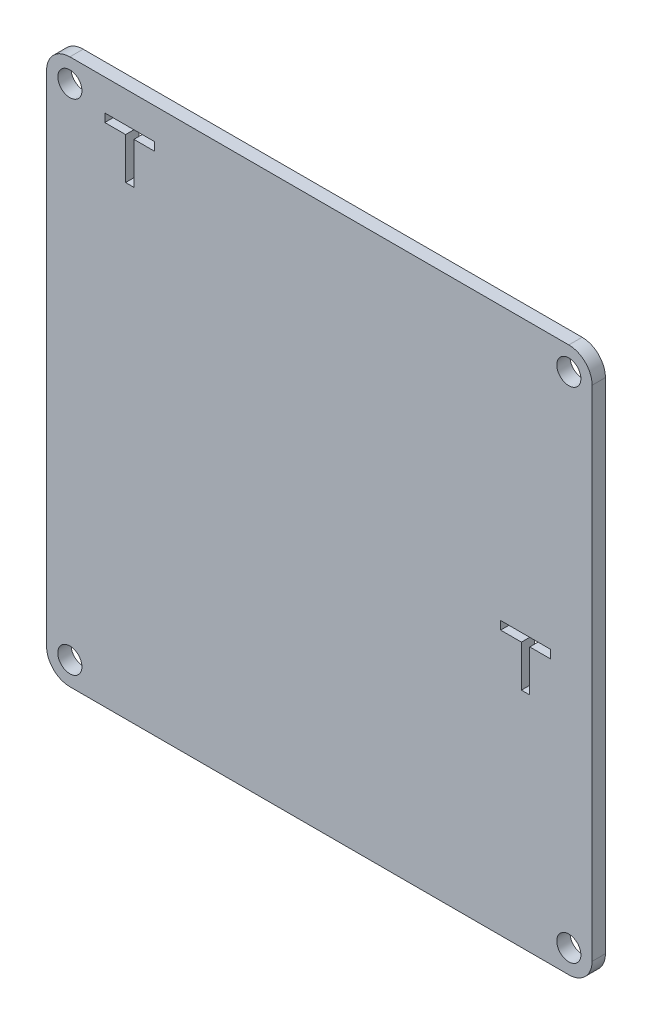
SolidWorks part; units mm, degrees
ref_plane "前视基准面" through (0, 0, 0) normal (0, 0, 1) x (1, 0, 0)
ref_plane "上视基准面" through (0, 0, 0) normal (0, 1, 0) x (1, 0, 0)
ref_plane "右视基准面" through (0, 0, 0) normal (1, 0, 0) x (0, 0, -1)
other "Configuration Table"
sketch "草图1" plane through (0, 0, 0) normal (0, 0, 1) x (1, 0, 0)
  line L1 (-30, 32.8) -> (30, 32.8)
  line L2 (32.8, 30) -> (32.8, -30)
  line L3 (30, -32.8) -> (-30, -32.8)
  line L4 (-32.8, -30) -> (-32.8, 30)
  line L5 (33, -30) -> (33, 30) construction
  arc A0 (30, 32.8) -> (32.8, 30) centre (30, 30) cw
  arc A1 (32.8, -30) -> (30, -32.8) centre (30, -30) cw
  arc A2 (-30, -32.8) -> (-32.8, -30) centre (-30, -30) cw
  arc A3 (-32.8, 30) -> (-30, 32.8) centre (-30, 30) cw
  arc A4 (-30, 33) -> (-33, 30) centre (-30, 30) ccw construction
  arc A6 (33, 30) -> (30, 33) centre (30, 30) ccw construction
  arc A7 (30, -33) -> (33, -30) centre (30, -30) ccw construction
  arc A8 (-33, -30) -> (-30, -33) centre (-30, -30) ccw construction
  circle A9 centre (-30, 30) radius 1.45
  circle A10 centre (30, 30) radius 1.45
  circle A11 centre (-30, -30) radius 1.45
  circle A12 centre (30, -30) radius 1.45
  dimension "D1" = 0.2
extrude "凸台-拉伸1" add sketch "草图1" along normal blind 1.6
sketch "草图2" plane through (0, 0, 1.6) normal (0, 0, 1) x (1, 0, 0)
  line L0 (-44.8384, 29.06) -> (-36.7288, 29.06) construction
  line L1 (-25.8, 29.06) -> (-19.8, 29.06)
  line L2 (-25.8, 29.06) -> (-25.8, 28.06)
  line L3 (-25.8, 28.06) -> (-23.3, 28.06)
  line L4 (-19.8, 29.06) -> (-19.8, 28.06)
  line L5 (-22.3, 28.06) -> (-19.8, 28.06)
  line L7 (-23.3, 28.06) -> (-23.3, 23.06)
  line L8 (-23.3, 23.06) -> (-22.3, 23.06)
  line L9 (-22.3, 28.06) -> (-22.3, 23.06)
  line L10 (-32.8, 30) -> (-32.8, -30) construction
  point P10 (-25.8, 28.56)
  dimension "D1" = 6
  dimension "D2" = 1
  dimension "D3" = 1
  dimension "D4" = 5
  dimension "D5" = 2.5
  dimension "D6" = 7
extrude "切除-拉伸1" cut sketch "草图2" against normal blind 1.6
sketch "草图3" plane through (0, 0, 1.6) normal (0, 0, 1) x (1, 0, 0)
  line L0 (25.3, -1) -> (27.8, -1)
  line L1 (21.8, 0) -> (27.8, 0)
  line L2 (21.8, 0) -> (21.8, -1)
  line L3 (21.8, -1) -> (24.3, -1)
  line L4 (27.8, 0) -> (27.8, -1)
  line L6 (24.3, -1) -> (24.3, -6)
  line L7 (24.3, -6) -> (25.3, -6)
  line L8 (25.3, -1) -> (25.3, -6)
  line L9 (32.8, -30) -> (32.8, 30) construction
  dimension "D1" = 5
  dimension "D2" = 1
  dimension "D3" = 1
  dimension "D4" = 6
  dimension "D5" = 2.5
  dimension "D6" = 5
extrude "切除-拉伸2" cut sketch "草图3" against normal blind 1.6
